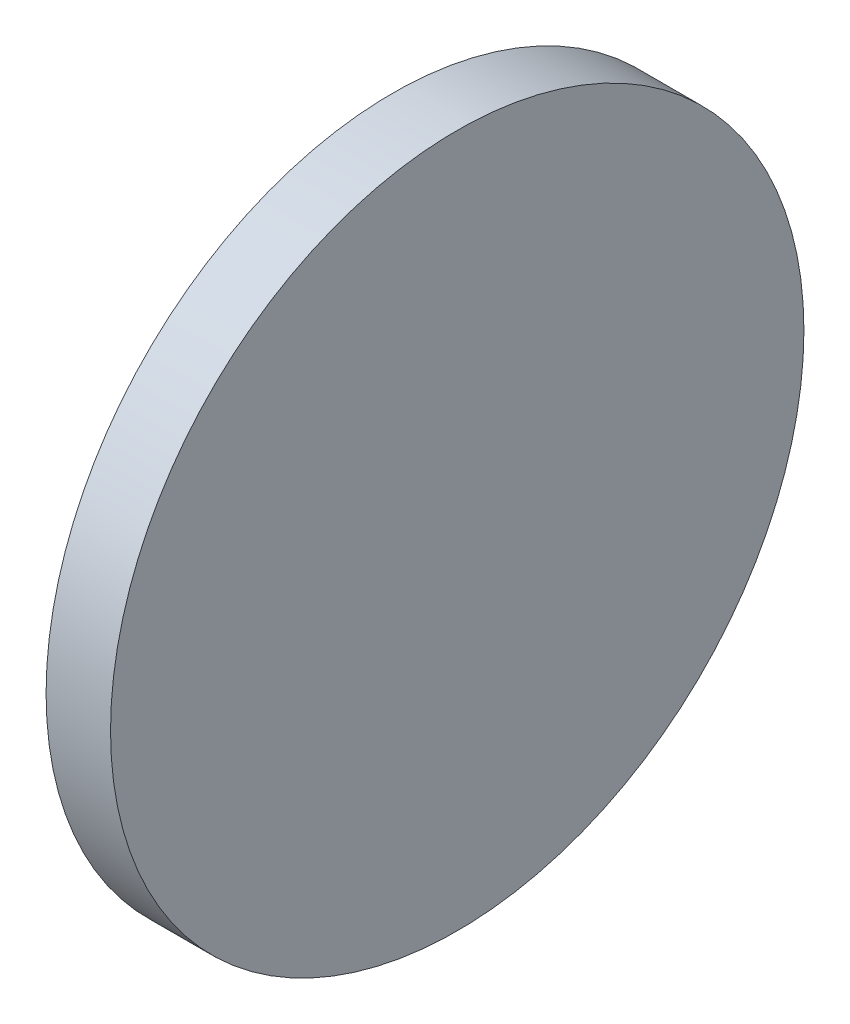
SolidWorks part; units mm, degrees
ref_plane "Front Plane" through (0, 0, 0) normal (0, 0, 1) x (1, 0, 0)
ref_plane "Top Plane" through (0, 0, 0) normal (0, 1, 0) x (1, 0, 0)
ref_plane "Right Plane" through (0, 0, 0) normal (1, 0, 0) x (0, 0, -1)
sketch "Sketch1" plane through (0, 0, 0) normal (0, 1, 0) x (1, 0, 0)
  line L1 (-0.7874, 8.4709) -> (0.7874, 8.4709)
  line L2 (-0.7874, 8.4709) -> (-0.7874, 0)
  line L3 (-0.7874, 0) -> (0.7874, 0)
  line L4 (0.7874, 8.4709) -> (0.7874, 0)
  dimension "D1" = 8.4709
  dimension "D2" = 1.5748
revolve "Revolve1" add sketch "Sketch1" angle 360 about L3
